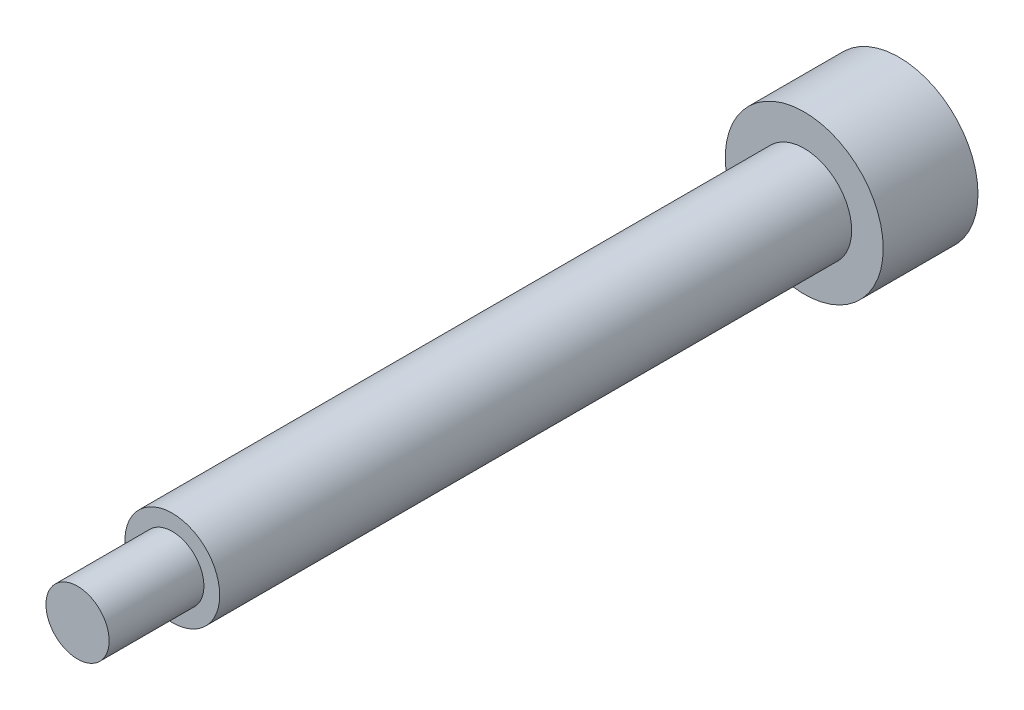
SolidWorks part; units mm, degrees
ref_plane "Alzado" through (0, 0, 0) normal (0, 0, 1) x (1, 0, 0)
ref_plane "Planta" through (0, 0, 0) normal (0, 1, 0) x (1, 0, 0)
ref_plane "Vista lateral" through (0, 0, 0) normal (1, 0, 0) x (0, 0, -1)
sketch "Croquis1" plane through (0, 0, 0) normal (0, 0, 1) x (1, 0, 0)
  circle A0 centre (0, 0) radius 5
  dimension "D1" = 10
extrude "Saliente-Extruir1" add sketch "Croquis1" along normal blind 6
sketch "Croquis2" plane through (0, 0, 0) normal (0, 0, -1) x (-1, 0, 0)
  line L1 (0, -1) -> (0.6069, -1)
  line L2 (1.118, -1) -> (0, -1)
  line L3 (0, -1) -> (-1.118, -1)
  arc A0 (1.118, -1) -> (-1.118, -1) centre (0, 0) ccw
  dimension "D1" = 3
extrude "Cortar-Extruir1" cut sketch "Croquis2" against normal blind 5 contours L2 A0 L3 L1
sketch "Croquis3" plane through (0, 0, 6) normal (0, 0, 1) x (1, 0, 0)
  circle A0 centre (0, 0) radius 3
  dimension "D1" = 6
extrude "Saliente-Extruir2" add sketch "Croquis3" along normal blind 40
sketch "Croquis4" plane through (0, 0, 46) normal (0, 0, 1) x (1, 0, 0)
  circle A0 centre (0, 0) radius 2
  dimension "D1" = 4
extrude "Saliente-Extruir3" add sketch "Croquis4" along normal blind 6
